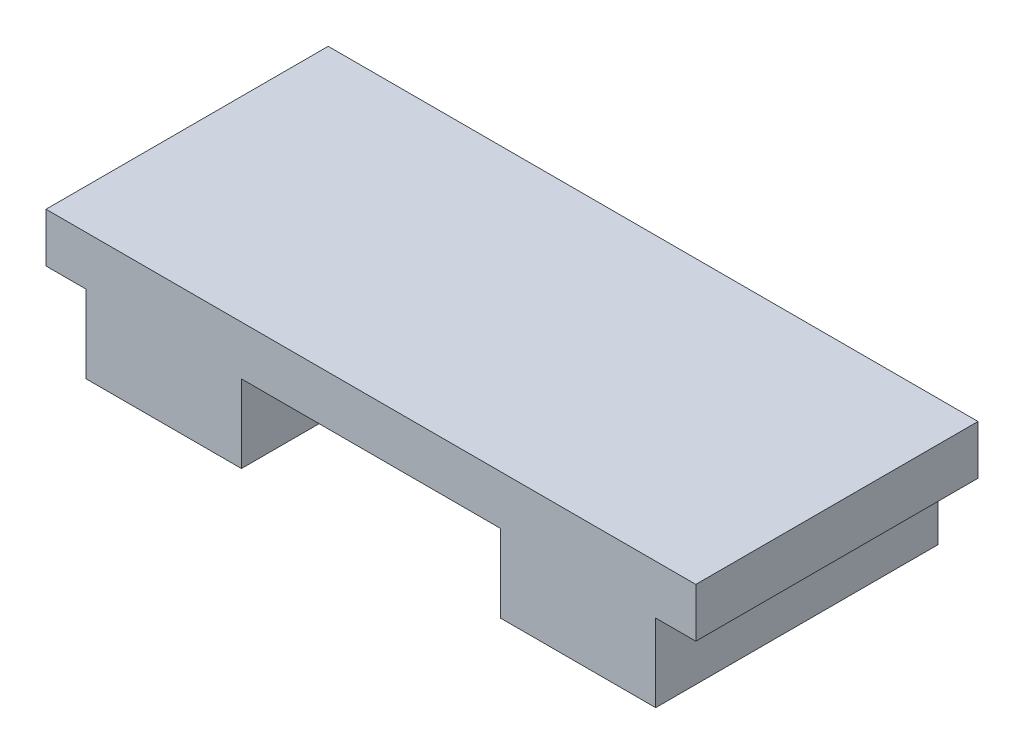
SolidWorks part; units mm, degrees
ref_plane "Front Plane" through (0, 0, 0) normal (0, 0, 1) x (1, 0, 0)
ref_plane "Top Plane" through (0, 0, 0) normal (0, 1, 0) x (1, 0, 0)
ref_plane "Right Plane" through (0, 0, 0) normal (1, 0, 0) x (0, 0, -1)
sketch "Sketch1" plane through (0, 0, 0) normal (0, 1, 0) x (1, 0, 0)
  line L0 (0, -55) -> (0, 55) construction
  line L1 (-11, -5.45) -> (-5, -5.45)
  line L2 (-11, -5.45) -> (-11, 5.45)
  line L3 (-11, 5.45) -> (-5, 5.45)
  line L4 (-5, -5.45) -> (-5, 5.45)
  line L5 (-11, -5.45) -> (-5, 5.45) construction
  line L6 (-11, 5.45) -> (-5, -5.45) construction
  line L7 (11, 5.45) -> (5, -5.45) construction
  line L8 (11, -5.45) -> (5, 5.45) construction
  line L9 (5, -5.45) -> (5, 5.45)
  line L10 (11, 5.45) -> (5, 5.45)
  line L11 (11, -5.45) -> (11, 5.45)
  line L12 (11, -5.45) -> (5, -5.45)
  point P0 (-8, 0)
  point P13 (8, 0)
  dimension "D1" = 6
  dimension "D2" = 10.9
  dimension "D3" = 10
extrude "Boss-Extrude1" add sketch "Sketch1" along normal blind 3
sketch "Sketch2" plane through (0, 3, 0) normal (0, 1, 0) x (1, 0, 0)
  line L1 (-12.55, -5.45) -> (12.55, -5.45)
  line L2 (-12.55, -5.45) -> (-12.55, 5.45)
  line L3 (-12.55, 5.45) -> (12.55, 5.45)
  line L4 (12.55, -5.45) -> (12.55, 5.45)
  line L5 (-12.55, -5.45) -> (12.55, 5.45) construction
  line L6 (-12.55, 5.45) -> (12.55, -5.45) construction
  point P0 (0, 0)
  dimension "D1" = 25.1
  dimension "D2" = 10.9
extrude "Boss-Extrude2" add sketch "Sketch2" along normal blind 1.9
